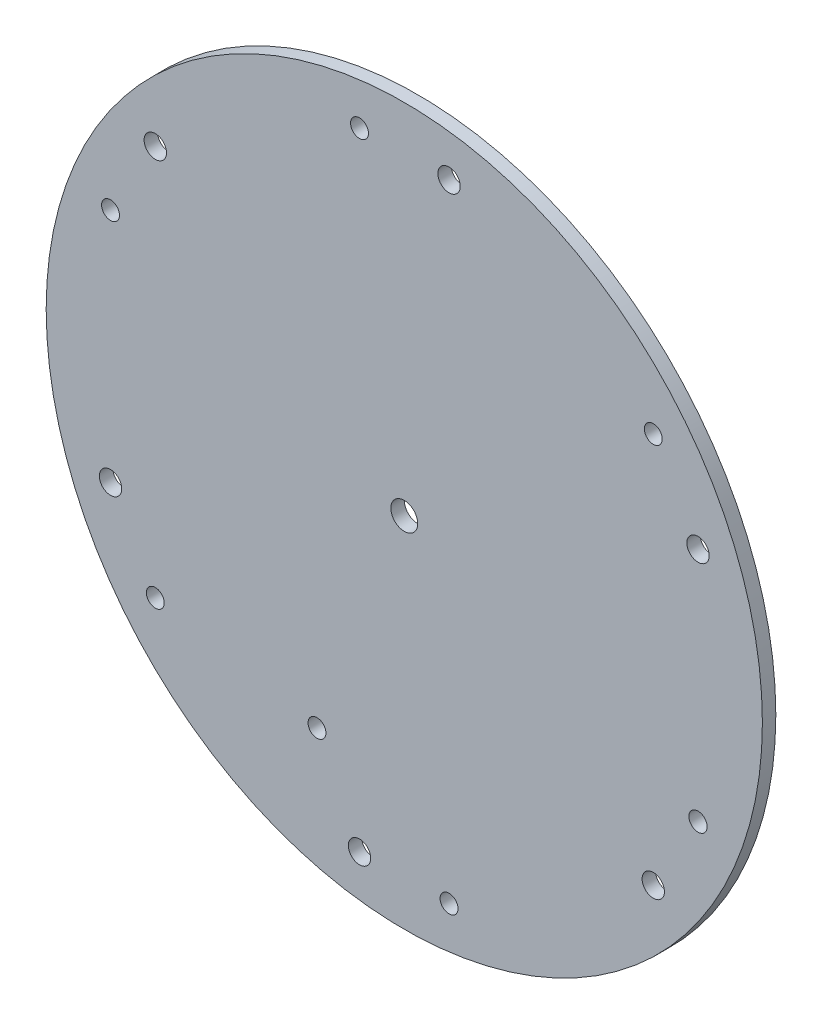
SolidWorks part; units mm, degrees
ref_plane "正面" through (0, 0, 0) normal (0, 0, 1) x (1, 0, 0)
ref_plane "平面" through (0, 0, 0) normal (0, 1, 0) x (1, 0, 0)
ref_plane "右側面" through (0, 0, 0) normal (1, 0, 0) x (0, 0, -1)
sketch "ｽｹｯﾁ1" plane through (0, 0, 0) normal (0, 0, 1) x (1, 0, 0)
  circle A1 centre (2197.5938, 1488.6153) radius 80
  circle A2 centre (2197.5938, 1488.6153) radius 3
  circle A3 centre (2187.5938, 1558.6153) radius 2
  circle A4 centre (2141.972, 1532.2756) radius 2.5
  circle A5 centre (2207.5938, 1558.6153) radius 2.5
  circle A6 centre (2131.972, 1514.9551) radius 2
  circle A7 centre (2131.972, 1462.2756) radius 2.5
  circle A8 centre (2141.972, 1444.9551) radius 2
  circle A9 centre (2178.0938, 1437.8362) radius 2
  circle A10 centre (2187.5938, 1418.6153) radius 2.5
  circle A11 centre (2207.5938, 1418.6153) radius 2
  circle A12 centre (2253.2156, 1444.9551) radius 2.5
  circle A13 centre (2263.2156, 1462.2756) radius 2.0395
  circle A14 centre (2263.2156, 1514.9551) radius 2.5
  circle A15 centre (2253.2156, 1532.2756) radius 2
extrude "ﾎﾞｽ - 押し出し1" add sketch "ｽｹｯﾁ1" along normal blind 3
